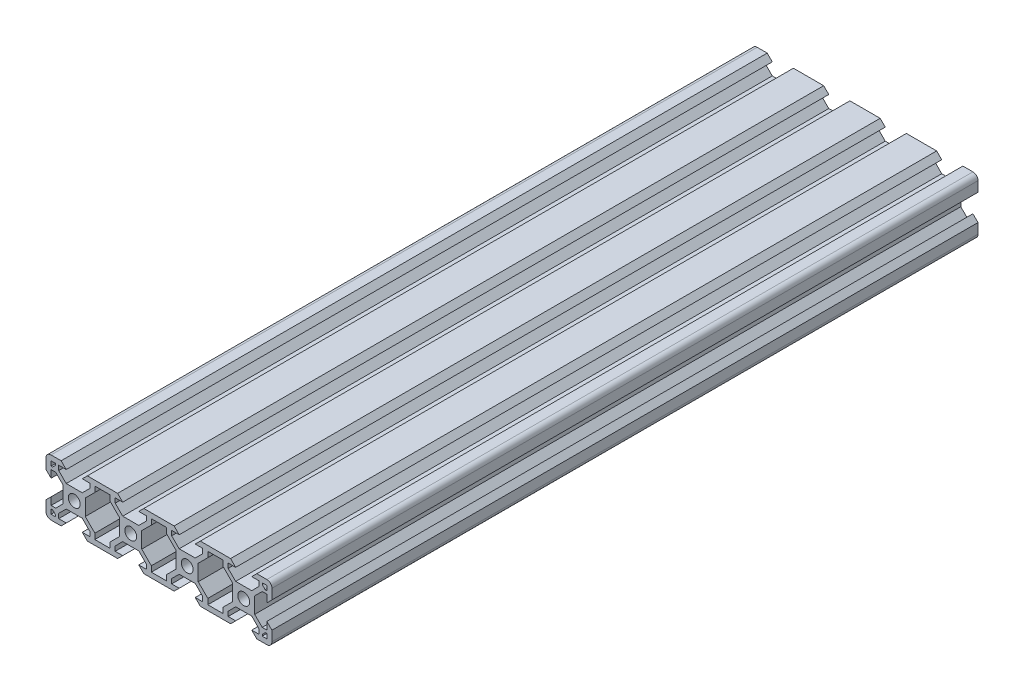
SolidWorks part; units mm, degrees
material "5052-H38, Barre (SS)"
ref_plane "Plan de face" through (0, 0, 0) normal (0, 0, 1) x (1, 0, 0)
ref_plane "Plan de dessus" through (0, 0, 0) normal (0, 1, 0) x (1, 0, 0)
ref_plane "Plan de droite" through (0, 0, 0) normal (1, 0, 0) x (0, 0, -1)
sketch "Esquisse1" plane through (0, 0, 0) normal (0, 0, 1) x (1, 0, 0)
  line L0 (0, 0) -> (0, 10) construction
  line L1 (0, 0) -> (-40, 0) construction
  line L2 (-40, 10) -> (-30, 0) construction
  line L3 (-30, 0) -> (-20, 10) construction
  line L4 (-20, 10) -> (-10, 0) construction
  line L5 (-10, 0) -> (0, 10) construction
  line L6 (-10, 0) -> (-10, 10) construction
  line L7 (-20, 10) -> (-20, 0) construction
  line L8 (-40, 0) -> (-40, 10) construction
  line L9 (-38.2, 10) -> (-34.64, 10)
  line L10 (-34.64, 10) -> (-32.84, 8.2)
  line L11 (-32.84, 8.2) -> (-35.4993, 8.2)
  line L12 (-35.4993, 8.2) -> (-35.4993, 6.56)
  line L13 (-35.4993, 6.56) -> (-32.84, 3.9007)
  line L14 (-32.84, 3.9007) -> (-27.16, 3.9007)
  line L15 (-30, 0) -> (-30, 10) construction
  line L16 (-33.9007, 2.84) -> (-33.9007, 0)
  line L17 (-36.56, 5.4993) -> (-33.9007, 2.84)
  line L18 (-38.2, 5.4993) -> (-36.56, 5.4993)
  line L19 (-38.2, 2.84) -> (-38.2, 5.4993)
  line L20 (-40, 4.64) -> (-38.2, 2.84)
  line L21 (-40, 8.2) -> (-40, 4.64)
  line L22 (-38.2, 8.2) -> (-38.2, 6.5693)
  line L23 (-38.2, 6.5693) -> (-37.63, 6.5693)
  line L24 (-37.63, 6.5693) -> (-36.5693, 7.63)
  line L25 (-36.5693, 7.63) -> (-36.5693, 8.2)
  line L26 (-36.5693, 8.2) -> (-38.2, 8.2)
  line L27 (-17.3, 6.2393) -> (-17.3, 8.2)
  line L28 (-13.9007, 2.84) -> (-17.3, 6.2393)
  line L29 (-13.9007, -2.84) -> (-13.9007, 2.84)
  line L30 (-14.64, 10) -> (-12.84, 8.2)
  line L31 (-12.84, 8.2) -> (-15.4993, 8.2)
  line L32 (-15.4993, 8.2) -> (-15.4993, 6.56)
  line L33 (-15.4993, 6.56) -> (-12.84, 3.9007)
  line L34 (-12.84, 3.9007) -> (-7.16, 3.9007)
  line L35 (-5.36, 10) -> (-7.16, 8.2)
  line L36 (-7.16, 8.2) -> (-4.5007, 8.2)
  line L37 (-4.5007, 8.2) -> (-4.5007, 6.56)
  line L38 (-4.5007, 6.56) -> (-7.16, 3.9007)
  line L39 (-5.36, 10) -> (5.36, 10)
  line L40 (-6.0993, -2.84) -> (-6.0993, 2.84)
  line L41 (-6.0993, 2.84) -> (-2.7, 6.2393)
  line L42 (-2.7, 6.2393) -> (-2.7, 8.2)
  line L43 (-2.7, 8.2) -> (2.7, 8.2)
  line L44 (-25.36, 10) -> (-27.16, 8.2)
  line L45 (-7.16, 3.9007) -> (-6.0993, 2.84) construction
  line L46 (-36.5693, -7.63) -> (-36.5693, -8.2)
  line L47 (-37.63, -6.5693) -> (-36.5693, -7.63)
  line L48 (-38.2, -6.5693) -> (-37.63, -6.5693)
  line L49 (-38.2, -8.2) -> (-38.2, -6.5693)
  line L50 (-27.16, 8.2) -> (-24.5007, 8.2)
  line L51 (-24.5007, 8.2) -> (-24.5007, 6.56)
  line L52 (-24.5007, 6.56) -> (-27.16, 3.9007)
  line L53 (-25.36, 10) -> (-14.64, 10)
  line L54 (-26.0993, -2.84) -> (-26.0993, 2.84)
  line L55 (-26.0993, 2.84) -> (-22.7, 6.2393)
  line L56 (-22.7, 6.2393) -> (-22.7, 8.2)
  line L57 (-22.7, 8.2) -> (-17.3, 8.2)
  line L58 (-27.16, 3.9007) -> (-26.0993, 2.84) construction
  line L59 (-26.0993, 2.84) -> (-26.0962, 2.8177) construction
  line L60 (-36.5693, -8.2) -> (-38.2, -8.2)
  line L61 (-26.0993, -2.84) -> (-22.7, -6.2393)
  line L62 (-22.7, -6.2393) -> (-22.7, -8.2)
  line L63 (-22.7, -8.2) -> (-17.3, -8.2)
  line L64 (-17.3, -6.2393) -> (-17.3, -8.2)
  line L65 (-13.9007, -2.84) -> (-17.3, -6.2393)
  line L66 (-2.7, -8.2) -> (2.7, -8.2)
  line L67 (-2.7, -6.2393) -> (-2.7, -8.2)
  line L68 (-6.0993, -2.84) -> (-2.7, -6.2393)
  line L69 (-5.36, -10) -> (5.36, -10)
  line L70 (-5.36, -10) -> (-7.16, -8.2)
  line L71 (-7.16, -8.2) -> (-4.5007, -8.2)
  line L72 (-4.5007, -8.2) -> (-4.5007, -6.56)
  line L73 (-4.5007, -6.56) -> (-7.16, -3.9007)
  line L74 (-12.84, -3.9007) -> (-7.16, -3.9007)
  line L75 (-15.4993, -6.56) -> (-12.84, -3.9007)
  line L76 (-15.4993, -8.2) -> (-15.4993, -6.56)
  line L77 (-12.84, -8.2) -> (-15.4993, -8.2)
  line L78 (-14.64, -10) -> (-12.84, -8.2)
  line L79 (-25.36, -10) -> (-14.64, -10)
  line L80 (-25.36, -10) -> (-27.16, -8.2)
  line L81 (-27.16, -8.2) -> (-24.5007, -8.2)
  line L82 (-24.5007, -8.2) -> (-24.5007, -6.56)
  line L83 (-24.5007, -6.56) -> (-27.16, -3.9007)
  line L84 (-32.84, -3.9007) -> (-27.16, -3.9007)
  line L85 (-35.4993, -6.56) -> (-32.84, -3.9007)
  line L86 (-35.4993, -8.2) -> (-35.4993, -6.56)
  line L87 (-32.84, -8.2) -> (-35.4993, -8.2)
  line L88 (-34.64, -10) -> (-32.84, -8.2)
  line L89 (-38.2, -10) -> (-34.64, -10)
  line L90 (-40, -8.2) -> (-40, -4.64)
  line L91 (-40, -4.64) -> (-38.2, -2.84)
  line L92 (-38.2, -2.84) -> (-38.2, -5.4993)
  line L93 (-38.2, -5.4993) -> (-36.56, -5.4993)
  line L94 (-36.56, -5.4993) -> (-33.9007, -2.84)
  line L95 (-33.9007, -2.84) -> (-33.9007, 0)
  line L96 (36.5693, 8.2) -> (38.2, 8.2)
  line L97 (36.5693, 7.63) -> (36.5693, 8.2)
  line L98 (37.63, 6.5693) -> (36.5693, 7.63)
  line L99 (38.2, 6.5693) -> (37.63, 6.5693)
  line L100 (38.2, 8.2) -> (38.2, 6.5693)
  line L101 (36.5693, -8.2) -> (38.2, -8.2)
  line L102 (36.5693, -7.63) -> (36.5693, -8.2)
  line L103 (37.63, -6.5693) -> (36.5693, -7.63)
  line L104 (38.2, -6.5693) -> (37.63, -6.5693)
  line L105 (38.2, -8.2) -> (38.2, -6.5693)
  line L106 (13.9007, -2.84) -> (17.3, -6.2393)
  line L107 (17.3, -6.2393) -> (17.3, -8.2)
  line L108 (22.7, -8.2) -> (17.3, -8.2)
  line L109 (22.7, -6.2393) -> (22.7, -8.2)
  line L110 (26.0993, -2.84) -> (22.7, -6.2393)
  line L111 (26.0993, -2.84) -> (26.0993, 2.84)
  line L112 (26.0993, 2.84) -> (22.7, 6.2393)
  line L113 (22.7, 6.2393) -> (22.7, 8.2)
  line L114 (22.7, 8.2) -> (17.3, 8.2)
  line L115 (17.3, 6.2393) -> (17.3, 8.2)
  line L116 (13.9007, 2.84) -> (17.3, 6.2393)
  line L117 (13.9007, -2.84) -> (13.9007, 2.84)
  line L118 (2.7, -6.2393) -> (2.7, -8.2)
  line L119 (6.0993, -2.84) -> (2.7, -6.2393)
  line L120 (6.0993, -2.84) -> (6.0993, 2.84)
  line L121 (6.0993, 2.84) -> (2.7, 6.2393)
  line L122 (2.7, 6.2393) -> (2.7, 8.2)
  line L123 (5.36, -10) -> (7.16, -8.2)
  line L124 (7.16, -8.2) -> (4.5007, -8.2)
  line L125 (4.5007, -8.2) -> (4.5007, -6.56)
  line L126 (4.5007, -6.56) -> (7.16, -3.9007)
  line L127 (12.84, -3.9007) -> (7.16, -3.9007)
  line L128 (15.4993, -6.56) -> (12.84, -3.9007)
  line L129 (15.4993, -8.2) -> (15.4993, -6.56)
  line L130 (12.84, -8.2) -> (15.4993, -8.2)
  line L131 (14.64, -10) -> (12.84, -8.2)
  line L132 (25.36, -10) -> (14.64, -10)
  line L133 (25.36, -10) -> (27.16, -8.2)
  line L134 (27.16, -8.2) -> (24.5007, -8.2)
  line L135 (24.5007, -8.2) -> (24.5007, -6.56)
  line L136 (24.5007, -6.56) -> (27.16, -3.9007)
  line L137 (32.84, -3.9007) -> (27.16, -3.9007)
  line L138 (35.4993, -6.56) -> (32.84, -3.9007)
  line L139 (35.4993, -8.2) -> (35.4993, -6.56)
  line L140 (32.84, -8.2) -> (35.4993, -8.2)
  line L141 (34.64, -10) -> (32.84, -8.2)
  line L142 (38.2, -10) -> (34.64, -10)
  line L143 (40, -8.2) -> (40, -4.64)
  line L144 (40, -4.64) -> (38.2, -2.84)
  line L145 (38.2, -2.84) -> (38.2, -5.4993)
  line L146 (38.2, -5.4993) -> (36.56, -5.4993)
  line L147 (36.56, -5.4993) -> (33.9007, -2.84)
  line L148 (33.9007, -2.84) -> (33.9007, 0)
  line L149 (33.9007, 2.84) -> (33.9007, 0)
  line L150 (36.56, 5.4993) -> (33.9007, 2.84)
  line L151 (38.2, 5.4993) -> (36.56, 5.4993)
  line L152 (38.2, 2.84) -> (38.2, 5.4993)
  line L153 (40, 4.64) -> (38.2, 2.84)
  line L154 (40, 8.2) -> (40, 4.64)
  line L155 (38.2, 10) -> (34.64, 10)
  line L156 (34.64, 10) -> (32.84, 8.2)
  line L157 (32.84, 8.2) -> (35.4993, 8.2)
  line L158 (35.4993, 8.2) -> (35.4993, 6.56)
  line L159 (35.4993, 6.56) -> (32.84, 3.9007)
  line L160 (32.84, 3.9007) -> (27.16, 3.9007)
  line L161 (24.5007, 6.56) -> (27.16, 3.9007)
  line L162 (24.5007, 8.2) -> (24.5007, 6.56)
  line L163 (27.16, 8.2) -> (24.5007, 8.2)
  line L164 (25.36, 10) -> (27.16, 8.2)
  line L165 (25.36, 10) -> (14.64, 10)
  line L166 (14.64, 10) -> (12.84, 8.2)
  line L167 (12.84, 8.2) -> (15.4993, 8.2)
  line L168 (15.4993, 8.2) -> (15.4993, 6.56)
  line L169 (15.4993, 6.56) -> (12.84, 3.9007)
  line L170 (12.84, 3.9007) -> (7.16, 3.9007)
  line L171 (4.5007, 6.56) -> (7.16, 3.9007)
  line L172 (4.5007, 8.2) -> (4.5007, 6.56)
  line L173 (7.16, 8.2) -> (4.5007, 8.2)
  line L174 (5.36, 10) -> (7.16, 8.2)
  circle A0 centre (-30, 0) radius 2.1
  circle A1 centre (-10, 0) radius 2.1
  arc A2 (-38.2, 10) -> (-40, 8.2) centre (-38.2, 8.2) ccw
  arc A3 (-38.2, -10) -> (-40, -8.2) centre (-38.2, -8.2) cw
  circle A4 centre (30, 0) radius 2.1
  circle A5 centre (10, 0) radius 2.1
  arc A6 (38.2, -10) -> (40, -8.2) centre (38.2, -8.2) ccw
  arc A7 (38.2, 10) -> (40, 8.2) centre (38.2, 8.2) cw
  point P21 (-37.0997, 7.0997)
  point P36 (-20, 8.2)
  point P47 (-10, 3.9007)
  point P54 (-6.6297, 3.3703)
  point P61 (-30, 3.9007)
  point P71 (-26.0993, 0)
  point P76 (-13.9007, 0)
  point P80 (-6.0993, 0)
  point P135 (0, -8.2)
  point P140 (0, 8.2)
  point P141 (0, -10)
  dimension "D3" = 4.2
  dimension "D4" = 4.2
  dimension "D1" = 40
  dimension "D2" = 10
  dimension "D5" = 5.68
  dimension "D6" = 1.5
  dimension "D7" = 1.64
  dimension "D8" = 1.8
  dimension "D9" = 1.07
  dimension "D11" = 5.4
extrude "Boss.-Extru.1" add sketch "Esquisse1" along normal mid plane 250
